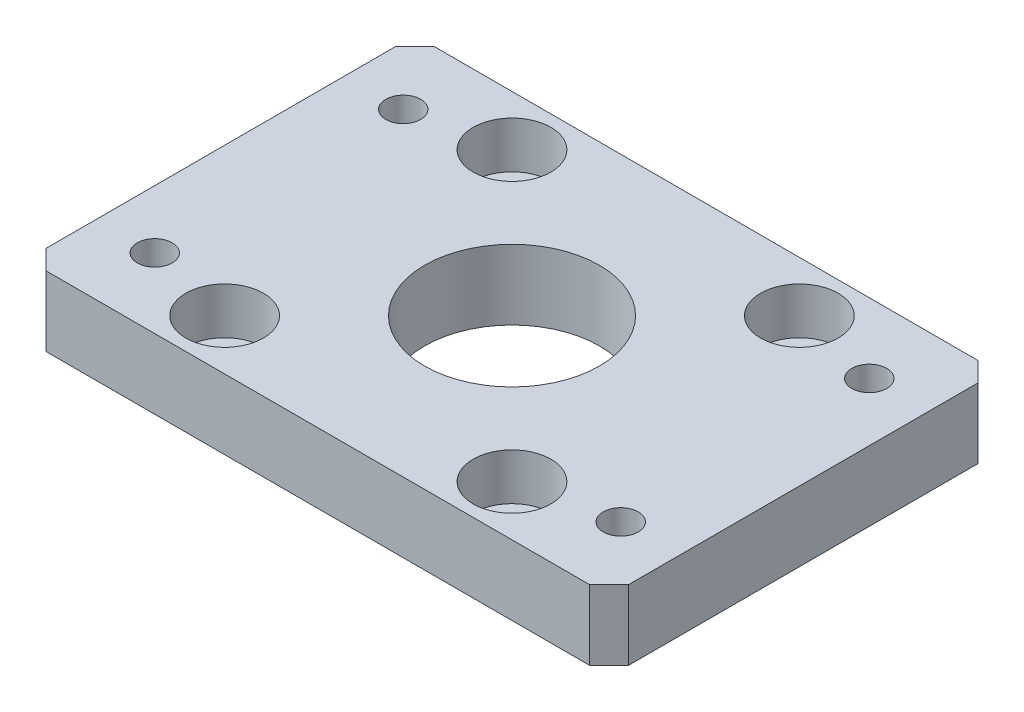
SolidWorks part; units mm, degrees
ref_plane "前基準面" through (0, 0, 0) normal (0, 0, 1) x (1, 0, 0)
ref_plane "上基準面" through (0, 0, 0) normal (0, 1, 0) x (1, 0, 0)
ref_plane "右基準面" through (0, 0, 0) normal (1, 0, 0) x (0, 0, -1)
sketch "草圖1" plane through (0, 0, 0) normal (0, 1, 0) x (1, 0, 0)
  line L0 (75, 50) -> (-75, -50) construction
  line L1 (-75, 50) -> (75, 50)
  line L2 (-75, 50) -> (-75, -50)
  line L3 (-75, -50) -> (75, -50)
  line L4 (75, 50) -> (75, -50)
  dimension "D1" = 150
  dimension "D2" = 100
extrude "伸長1" add sketch "草圖1" along normal blind 18
chamfer "導角1" distance 5 angle 45 4 edges at (75, 9, 50) (75, 9, -50) (-75, 9, 50) (-75, 9, -50)
hole_wizard "M8 六角承窩頭蓋螺釘的柱孔1" positions "草圖13" profile "草圖12" counterbore size "M8" standard "ISO" end condition through all
sketch "草圖13" plane through (-62.5, 0, 50) normal (0, -1, 0) x (1, 0, 0)
  line L4 (137.5, -5) -> (137.5, -95) construction
  line L5 (-12.5, -95) -> (-12.5, -5) construction
  line L6 (62.5, -30.9257) -> (62.5, -50) construction
  line L7 (62.5, -50) -> (86.7368, -50) construction
  point P1 (2.5, -82)
  point P3 (2.5, -18)
  point P21 (122.5, -18)
  point P23 (122.5, -82)
  dimension "D1" = 15
  dimension "D2" = 64
  dimension "D3" = 15
sketch "草圖12" plane through (-60, 0, -32) normal (1, 0, 0) x (0, 0, -1)
  line L0 (0, 0) -> (0, 18)
  line L1 (0, 18) -> (4.5, 18)
  line L3 (4.5, 18) -> (4.5, 8)
  line L4 (4.5, 8) -> (7.5, 8)
  line L5 (7.5, 8) -> (7.5, 0)
  line L7 (7.5, 0) -> (0, 0)
  line L11 (0, -6.35) -> (0, 107.95) construction
  dimension "貫穿孔直徑" = 9
  dimension "貫穿孔深度" = 18
  dimension "柱孔直徑" = 15
  dimension "柱孔深度" = 8
hole_wizard "M12 六角承窩頭蓋螺釘的柱孔5" positions "草圖15" profile "草圖14" counterbore size "M12" standard "ISO" end condition through all
sketch "草圖15" plane through (0, 18, 0) normal (0, 1, 0) x (-1, 0, 0)
  line L0 (-75, 0) -> (0, 0) construction
  line L1 (-75, 45) -> (-75, -45) construction
  line L2 (0, 0) -> (0, 34.5205) construction
  point P0 (37, -37)
  point P1 (-37, -37)
  point P3 (-37, 37)
  point P5 (37, 37)
  dimension "D1" = 74
  dimension "D2" = 74
sketch "草圖14" plane through (-37, 18, -37) normal (1, 0, 0) x (0, 0, 1)
  line L0 (0, 0) -> (0, 18)
  line L1 (0, 18) -> (6.75, 18)
  line L3 (6.75, 18) -> (6.75, 12)
  line L4 (6.75, 12) -> (10, 12)
  line L5 (10, 12) -> (10, 0)
  line L7 (10, 0) -> (0, 0)
  line L11 (0, -6.35) -> (0, 107.95) construction
  dimension "貫穿孔直徑" = 13.5
  dimension "貫穿孔深度" = 18
  dimension "柱孔直徑" = 20
  dimension "柱孔深度" = 12
sketch "草圖16" plane through (0, 18, 0) normal (0, 1, 0) x (1, 0, 0)
  line L0 (37, 37) -> (-37, -37) construction
  circle A0 centre (0, 0) radius 22.5
  dimension "D1" = 45
extrude "除料-伸長3" cut sketch "草圖16" against normal through all
